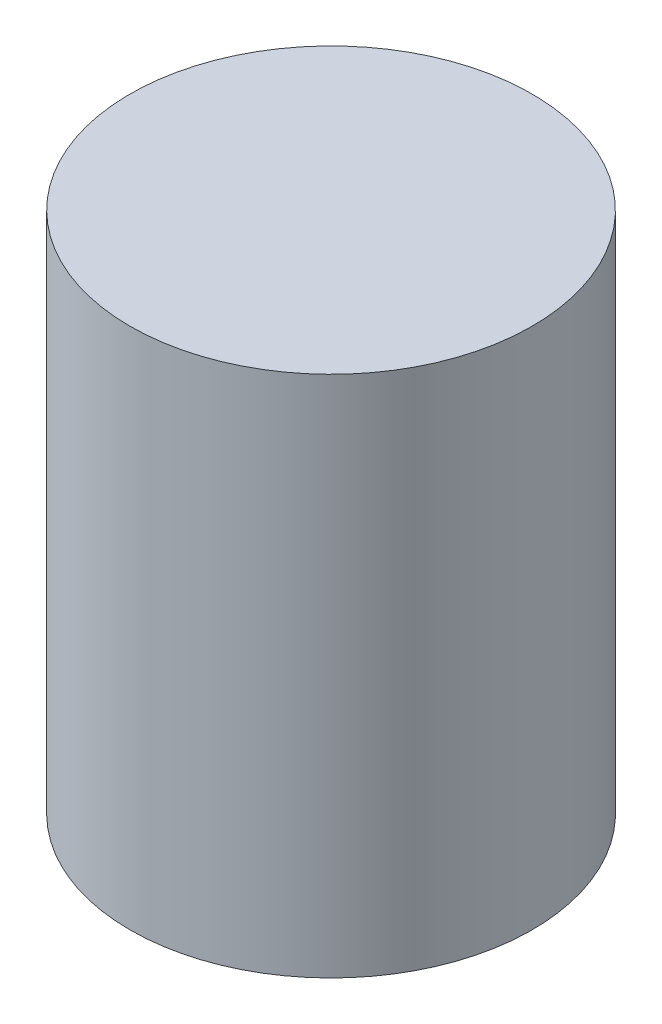
SolidWorks part; units mm, degrees
ref_plane "前视基准面" through (0, 0, 0) normal (0, 0, 1) x (1, 0, 0)
ref_plane "上视基准面" through (0, 0, 0) normal (0, 1, 0) x (1, 0, 0)
ref_plane "右视基准面" through (0, 0, 0) normal (1, 0, 0) x (0, 0, -1)
sketch "草图1" plane through (0, 0, 0) normal (0, 1, 0) x (1, 0, 0)
  circle A0 centre (-38.622, 12.5316) radius 4.5
extrude "凸台-拉伸1" add sketch "草图1" along normal blind 11.7
